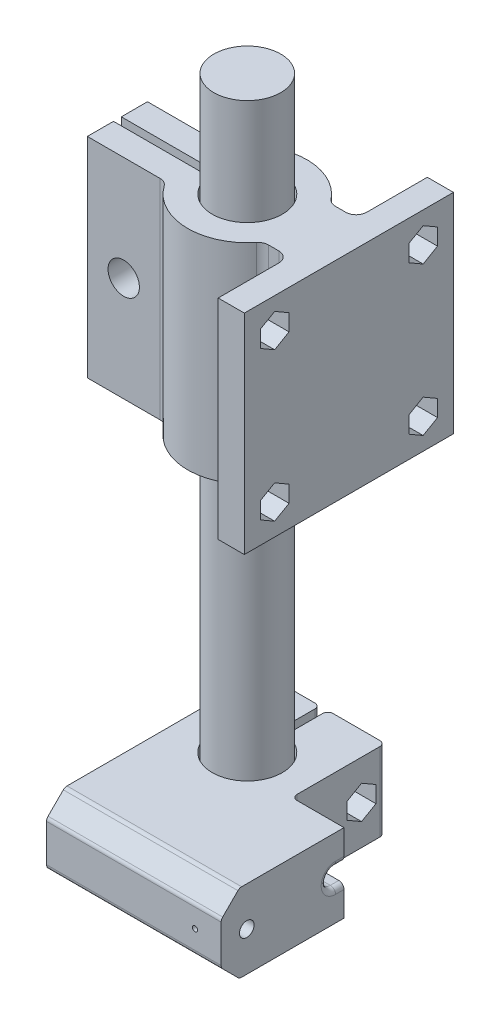
SolidWorks part; units mm, degrees
ref_plane "Front Plane" through (0, 0, 0) normal (0, 0, 1) x (1, 0, 0)
ref_plane "Top Plane" through (0, 0, 0) normal (0, 1, 0) x (1, 0, 0)
ref_plane "Right Plane" through (0, 0, 0) normal (1, 0, 0) x (0, 0, -1)
sketch "Sketch1" plane through (0, 0, 0) normal (0, 1, 0) x (1, 0, 0)
  circle A0 centre (0, 0) radius 6.4
  dimension "D1" = 12.8
extrude "Boss-Extrude1" add sketch "Sketch1" along normal blind 40 and the other way blind 80
sketch "Sketch2" plane through (0, 0, 0) normal (0, 1, 0) x (1, 0, 0)
  line L0 (-9.8437, 5.75) -> (-24.8437, 5.75)
  line L1 (-24.8437, 5.75) -> (-24.8437, 0.75)
  line L2 (0, 6.4) -> (0, 0) construction
  line L3 (-39.5441, 0) -> (14.434, 0) construction
  line L4 (9.434, -6.4) -> (14.434, -6.4)
  line L5 (-24.8437, 0.75) -> (-6.6579, 0.75)
  line L6 (-24.8437, -0.75) -> (-6.6579, -0.75)
  line L7 (-24.8437, -5.75) -> (-24.8437, -0.75)
  line L8 (-9.8437, -5.75) -> (-24.8437, -5.75)
  line L9 (14.434, -6.4) -> (14.434, 6.4)
  line L10 (14.434, 6.4) -> (9.434, 6.4)
  arc A0 (9.434, 6.4) -> (-9.8437, 5.75) centre (0, 0) ccw
  circle A1 centre (0, 0) radius 6.4 construction
  arc A2 (-6.6579, -0.75) -> (-6.6579, 0.75) centre (0, 0) ccw
  arc A3 (9.434, -6.4) -> (-9.8437, -5.75) centre (0, 0) cw
  point P13 (0, 3.2)
  point P20 (0, -3.2)
  point P21 (6.7, 0)
  dimension "D1" = 5
  dimension "D2" = 0.3
  dimension "D6" = 5
  dimension "D3" = 0.75
  dimension "D4" = 5
  dimension "D5" = 15
extrude "Boss-Extrude2" add sketch "Sketch2" along normal blind 20 and the other way blind 20 separate body
sketch "Sketch6" plane through (14.434, 0, 0) normal (1, 0, 0) x (0, 0, -1)
  line L0 (-6.4, -20) -> (6.4, -20) construction
  line L1 (-20, -20) -> (20, -20)
  line L2 (-20, -20) -> (-20, 20)
  line L3 (-20, 20) -> (20, 20)
  line L4 (20, -20) -> (20, 20)
  line L5 (-20, -20) -> (20, 20) construction
  line L6 (-20, 20) -> (20, -20) construction
  point P0 (0, 0)
  dimension "D1" = 40
extrude "Boss-Extrude6" add sketch "Sketch6" along normal blind 10
ref_plane "Plane1" through (0, 0, 0) normal (0, 0, -1) x (-1, 0, 0)
sketch "Sketch7" plane through (0, 0, 0) normal (0, 0, -1) x (-1, 0, 0)
  line L0 (0, 0) -> (-105.5276, 0) construction
  line L1 (-24.434, -6.4) -> (-29.434, -6.4)
  line L3 (-24.434, 20) -> (-24.434, -20) construction
  line L4 (-48.7116, -5.75) -> (-63.7116, -5.75)
  line L5 (-63.7116, -5.75) -> (-63.7116, -0.75)
  line L6 (-63.7116, -0.75) -> (-45.5259, -0.75)
  line L7 (-24.434, -6.4) -> (-24.434, 6.4)
  line L8 (-63.7116, 0.75) -> (-45.5259, 0.75)
  line L9 (-63.7116, 5.75) -> (-63.7116, 0.75)
  line L10 (-48.7116, 5.75) -> (-63.7116, 5.75)
  line L11 (-24.434, 6.4) -> (-29.434, 6.4)
  circle A0 centre (-38.868, 0) radius 6.4 construction
  arc A1 (-48.7116, -5.75) -> (-29.434, -6.4) centre (-38.868, 0) ccw
  arc A2 (-45.5259, -0.75) -> (-45.5259, 0.75) centre (-38.868, 0) ccw
  arc A3 (-48.7116, 5.75) -> (-29.434, 6.4) centre (-38.868, 0) cw
  point P15 (-38.868, -6.4)
  point P19 (-24.434, 0)
  point P21 (-38.868, 6.4)
  dimension "D1" = 12.8
  dimension "D2" = 5
  dimension "D4" = 0.3
  dimension "D7" = 15
  dimension "D3" = 5
  dimension "D5" = 0.75
  dimension "D6" = 5
extrude "Boss-Extrude7" add sketch "Sketch7" along normal blind 20 and the other way blind 20
fillet "Fillet4" radius 2 4 edges
fillet "Fillet5" radius 2 8 edges at (29.434, -6.4, 0) (29.434, 6.4, 0) (48.7116, 5.75, 0) (48.7116, -5.75, 0) (9.434, 0, 6.4) (9.434, 0, -6.4) (-9.8437, 0, -5.75) (-9.8437, 0, 5.75)
sketch "Sketch9" plane through (0, 0, 5.75) normal (0, 0, 1) x (1, 0, 0)
  line L0 (-10.9315, 0) -> (-24.8437, 0) construction
  line L1 (-24.8437, -20) -> (-24.8437, 20) construction
  line L3 (-10.9315, -20) -> (-10.9315, 20) construction
  circle A1 centre (-17.8876, 0) radius 3
  dimension "D1" = 6
extrude "Cut-Extrude1" cut sketch "Sketch9" against normal up to surface (11.5 mm away) up to face at (-17.8876, 0, -5.75)
sketch "Sketch10" plane through (0, -5.75, 0) normal (0, -1, 0) x (-1, 0, 0)
  line L0 (-63.7116, 0) -> (-49.7995, 0) construction
  line L1 (-63.7116, -20) -> (-63.7116, 20) construction
  line L2 (-49.7995, -20) -> (-49.7995, 20) construction
  circle A0 centre (-56.7555, 0) radius 2.5
  dimension "D1" = 5
extrude "Cut-Extrude2" cut sketch "Sketch10" against normal up to surface (11.5 mm away) up to face at (56.7555, 5.75, 0)
sketch "Sketch13" plane through (0, -80, 0) normal (0, -1, 0) x (1, 0, 0)
  line L0 (11.7, -14.6579) -> (11.7, 26.7)
  line L1 (11.7, -14.6579) -> (0.75, -14.6579)
  line L2 (0, -14.6579) -> (0, 33.0338) construction
  line L3 (-11.7, 26.7) -> (11.7, 26.7)
  line L5 (0.75, -14.6579) -> (0.75, -6.6579)
  line L6 (-0.75, -14.6579) -> (-0.75, -6.6579)
  line L8 (-11.7, -14.6579) -> (-0.75, -14.6579)
  line L9 (-11.7, -14.6579) -> (-11.7, 26.7)
  arc A0 (0.75, -6.6579) -> (-0.75, -6.6579) centre (0, 0) ccw
  circle A1 centre (0, 0) radius 6.4 construction
  point P13 (6.7, 0)
  point P18 (-6.7, 0)
  point P19 (0, 6.7)
  dimension "D1" = 0.3
  dimension "D4" = 5
  dimension "D2" = 0.75
  dimension "D3" = 8
  dimension "D5" = 20
extrude "Boss-Extrude8" add sketch "Sketch13" along normal blind 7.5 and the other way blind 7.5 separate body
sketch "Sketch22" [suppressed] plane through (0, -70, 0) normal (0, 1, 0) x (1, 0, 0)
  line L0 (-3, -26.7) -> (-11.7, -18) construction
  line L1 (3, -26.7) -> (-3, -26.7) construction
  line L2 (11.7, -18) -> (3, -26.7) construction
  line L3 (-3, -26.7) -> (-11.7, -18)
  line L4 (3, -26.7) -> (-3, -26.7)
  line L5 (11.7, -18) -> (3, -26.7)
  line L6 (-11.7, -18) -> (-11.7, -10.7)
  line L7 (-11.7, -26.7) -> (-11.7, 14.625) construction
  line L8 (-11.7, -10.7) -> (11.7, -10.7)
  line L9 (11.7, 14.625) -> (11.7, -26.7) construction
  line L10 (11.7, -10.7) -> (11.7, -18)
  arc A1 (-1, 6.625) -> (1, 6.625) centre (0, 0) ccw construction
  point P10 (0, -6.7)
  dimension "D1" = 4
extrude "Boss-Extrude10" [suppressed] add sketch "Sketch22" along normal blind 10
sketch "Sketch23" [suppressed] plane through (0, 0, 10.7) normal (0, 0, -1) x (-1, 0, 0)
  line L0 (0, -75) -> (0, -65) construction
  line L1 (-11.7, -75) -> (11.7, -75) construction
  line L2 (-11.7, -65) -> (11.7, -65) construction
  line L3 (-11.7, -65) -> (-11.7, -75) construction
  circle A0 centre (0, -70) radius 0.5
  dimension "D1" = 1
extrude "Cut-Extrude11" [suppressed] cut sketch "Sketch23" against normal up to next
sketch "Sketch24" [suppressed] plane through (0, 0, 10.7) normal (0, 0, -1) x (-1, 0, 0)
  circle A0 centre (0, -70) radius 1.75
  dimension "D1" = 3.5
extrude "Cut-Extrude12" [suppressed] cut sketch "Sketch24" against normal blind 8
sketch "Sketch25" [suppressed] plane through (0, -65, 0) normal (0, 1, 0) x (1, 0, 0)
  line L0 (0, -26.7) -> (0, -18.7) construction
  line L1 (-3, -26.7) -> (3, -26.7) construction
  line L2 (1.75, -18.7) -> (-1.75, -18.7) construction
  circle A0 centre (0, -22.7) radius 1.45
  dimension "D1" = 2.9
extrude "Cut-Extrude13" [suppressed] cut sketch "Sketch25" against normal blind 5
sketch "Sketch26" [suppressed] plane through (0, -65, 0) normal (0, 1, 0) x (1, 0, 0)
  line L0 (0, -5.5763) -> (0, -13.6517) construction
  line L2 (1.75, -5.5763) -> (1.75, -13.6517)
  line L4 (-1.75, -5.5763) -> (-1.75, -13.6517)
  arc A0 (1.75, -5.5763) -> (-1.75, -5.5763) centre (0, -5.5763) ccw
  arc A1 (-1.75, -13.6517) -> (1.75, -13.6517) centre (0, -13.6517) ccw
  point P5 (0, -9.614)
  dimension "D1" = 3.5
extrude "Cut-Extrude14" [suppressed] cut sketch "Sketch26" against normal blind 5
fillet "Fillet6" radius 1 2 edges at (-11.7, -80, -14.6579) (11.7, -80, -14.6579)
fillet "Fillet7" radius 1 2 edges at (0.75, -80, -14.6579) (-0.75, -80, -14.6579)
sketch "Sketch17" plane through (-11.7, 0, 0) normal (-1, 0, 0) x (0, 0, 1)
  line L0 (-13.6579, -80) -> (-6.6579, -80) construction
  line L3 (-6.6579, -72.5) -> (-6.6579, -87.5) construction
  line L4 (-13.6579, -72.5) -> (-13.6579, -87.5) construction
  circle A0 centre (-10.1579, -80) radius 1.55
  dimension "D1" = 3.1
extrude "Cut-Extrude8" cut sketch "Sketch17" against normal up to surface (23.4 mm away) up to face at (11.7, -80, 6.5211)
sketch "Sketch18" plane through (11.7, 0, 0) normal (1, 0, 0) x (0, 0, -1)
  line L0 (12.9079, -78.4123) -> (12.9079, -81.5877)
  line L1 (7.4079, -78.4123) -> (7.4079, -81.5877)
  line L2 (12.9079, -78.4123) -> (10.1579, -76.8246)
  line L3 (10.1579, -76.8246) -> (7.4079, -78.4123)
  line L4 (7.4079, -81.5877) -> (10.1579, -83.1754)
  line L5 (10.1579, -83.1754) -> (12.9079, -81.5877)
  line L6 (12.9079, -80) -> (7.4079, -80) construction
  circle A0 centre (10.1579, -80) radius 1.25 construction
  circle A1 centre (10.1579, -80) radius 1.55 construction
  dimension "D3" = 2.5
  dimension "D1" = 5.5
  dimension "D2" = 120
  dimension "D4" = 2.75
extrude "Cut-Extrude9" cut sketch "Sketch18" against normal blind 5
sketch "Sketch19" plane through (0, -80, 0) normal (0, -1, 0) x (-1, 0, 0)
  circle A1 centre (0, 0) radius 6.4
  circle A2 centre (0, 0) radius 6.4
  dimension "D1" = 0
extrude "Boss-Extrude9" add sketch "Sketch19" along normal blind 10
fillet "Fillet9" [suppressed] radius 1
sketch "Sketch27" plane through (11.7, 0, 0) normal (1, 0, 0) x (0, 0, -1)
  line L0 (-26.7, -80) -> (13.6579, -80) construction
  line L3 (-26.7, -72.5) -> (-26.7, -87.5) construction
  line L4 (13.6579, -87.5) -> (13.6579, -72.5) construction
  line L5 (-23.2, -72.5) -> (-26.7, -76)
  line L6 (13.6579, -72.5) -> (-26.7, -72.5) construction
  line L7 (-26.7, -76) -> (-26.7, -84)
  line L8 (-23.2, -72.5) -> (-3.2, -72.5)
  line L9 (-3.2, -72.5) -> (-3.2, -87.5)
  line L10 (-23.2, -87.5) -> (-3.2, -87.5)
  line L11 (-23.2, -87.5) -> (-26.7, -84)
  point P13 (-3.2, -80)
  dimension "D1" = 45
  dimension "D2" = 20
  dimension "D3" = 4
extrude "Boss-Extrude11" add sketch "Sketch27" along normal blind 10
sketch "Sketch28" plane through (11.7, 0, 0) normal (1, 0, 0) x (0, 0, -1)
  line L0 (-26.7, -72.5) -> (-26.7, -76) construction
  line L1 (-26.7, -76) -> (-23.2, -72.5) construction
  line L2 (-23.2, -72.5) -> (-26.7, -72.5) construction
  line L3 (-26.7, -87.5) -> (-23.2, -87.5) construction
  line L4 (-23.2, -87.5) -> (-26.7, -84) construction
  line L5 (-26.7, -84) -> (-26.7, -87.5) construction
  line L6 (-26.7, -72.5) -> (-26.7, -76)
  line L7 (-26.7, -76) -> (-23.2, -72.5)
  line L8 (-23.2, -72.5) -> (-26.7, -72.5)
  line L9 (-26.7, -87.5) -> (-23.2, -87.5)
  line L10 (-23.2, -87.5) -> (-26.7, -84)
  line L11 (-26.7, -84) -> (-26.7, -87.5)
extrude "Cut-Extrude15" cut sketch "Sketch28" against normal up to next (23.4 mm away)
sketch "Sketch29" plane through (0, 0, 3.2) normal (0, 0, -1) x (-1, 0, 0)
  line L0 (-11.7, -80) -> (-21.7, -80) construction
  line L1 (-11.7, -87.5) -> (-11.7, -72.5) construction
  line L2 (-21.7, -87.5) -> (-21.7, -72.5) construction
  circle A0 centre (-16.7, -80) radius 0.5
  dimension "D1" = 1
extrude "Cut-Extrude16" cut sketch "Sketch29" against normal up to next (23.5 mm away)
sketch "Sketch30" plane through (0, 0, 3.2) normal (0, 0, -1) x (-1, 0, 0)
  circle A0 centre (-16.7, -80) radius 1.75
  dimension "D1" = 3.5
extrude "Cut-Extrude17" cut sketch "Sketch30" against normal blind 8
fillet "Fillet10" radius 1 5 edges at (5, -87.5, 23.2) (5, -84, 26.7) (5, -76, 26.7) (5, -72.5, 23.2) (11.7, -80, 3.2)
sketch "Sketch31" plane through (21.7, 0, 0) normal (1, 0, 0) x (0, 0, -1)
  line L0 (-3.2, -80) -> (-26.7, -80) construction
  line L1 (-3.2, -87.5) -> (-3.2, -72.5) construction
  line L2 (-26.7, -76.4142) -> (-26.7, -83.5858) construction
  circle A0 centre (-21.7969, -80) radius 1.4
  dimension "D1" = 2.8
extrude "Cut-Extrude18" cut sketch "Sketch31" against normal blind 5
sketch "Sketch32" plane through (21.7, 0, 0) normal (1, 0, 0) x (0, 0, -1)
  line L0 (-1.3874, -80) -> (-4.8189, -80) construction
  line L2 (-1.3874, -81.75) -> (-4.8189, -81.75)
  line L3 (-1.3874, -78.25) -> (-4.8189, -78.25)
  arc A0 (-1.3874, -81.75) -> (-1.3874, -78.25) centre (-1.3874, -80) ccw
  arc A1 (-4.8189, -78.25) -> (-4.8189, -81.75) centre (-4.8189, -80) ccw
  point P4 (-3.1032, -80)
  dimension "D1" = 3.5
extrude "Cut-Extrude19" cut sketch "Sketch32" against normal blind 5
fillet "Fillet11" radius 1 3 edges at (21.7, -81.75, 4.0095) (21.7, -80, 6.5689) (21.7, -78.25, 4.0095)
sketch "Sketch33" plane through (14.434, 0, 0) normal (-1, 0, 0) x (0, 0, 1)
  line L0 (14.2, 20) -> (14.2, 8.4) construction
  line L1 (8.4, 20) -> (20, 20) construction
  line L2 (20, 8.4) -> (-20, 8.4) construction
  line L3 (20, 0) -> (8.4, 0) construction
  line L4 (20, 20) -> (20, -20) construction
  line L5 (8.4, 20) -> (8.4, -20) construction
  line L6 (0, 20) -> (0, -20) construction
  line L7 (-5.75, -20) -> (-0.75, -20) construction
  line L8 (-5.75, 20) -> (-0.75, 20) construction
  circle A0 centre (14.2, 14.2) radius 1.5
  circle A1 centre (14.2, -14.2) radius 1.5
  circle A2 centre (-14.2, -14.2) radius 1.5
  circle A3 centre (-14.2, 14.2) radius 1.5
  dimension "D1" = 3
extrude "Cut-Extrude20" cut sketch "Sketch33" against normal blind 10
sketch "Sketch34" plane through (14.434, 0, 0) normal (-1, 0, 0) x (0, 0, 1)
  line L0 (16.95, -12.6123) -> (16.95, -15.7877)
  line L1 (11.45, -12.6123) -> (11.45, -15.7877)
  line L2 (16.95, -12.6123) -> (14.2, -11.0246)
  line L3 (14.2, -11.0246) -> (11.45, -12.6123)
  line L4 (11.45, -15.7877) -> (14.2, -17.3754)
  line L5 (14.2, -17.3754) -> (16.95, -15.7877)
  line L6 (16.95, -14.2) -> (11.45, -14.2) construction
  line L7 (20, 0) -> (8.4, 0) construction
  line L8 (20, 20) -> (20, -20) construction
  line L9 (8.4, 20) -> (8.4, -20) construction
  line L10 (16.95, 14.2) -> (11.45, 14.2) construction
  line L11 (14.2, 17.3754) -> (16.95, 15.7877)
  line L12 (11.45, 15.7877) -> (14.2, 17.3754)
  line L13 (14.2, 11.0246) -> (11.45, 12.6123)
  line L14 (16.95, 12.6123) -> (14.2, 11.0246)
  line L15 (11.45, 12.6123) -> (11.45, 15.7877)
  line L16 (16.95, 12.6123) -> (16.95, 15.7877)
  line L17 (0, 20) -> (0, -20) construction
  line L18 (-5.75, -20) -> (-0.75, -20) construction
  line L19 (-5.75, 20) -> (-0.75, 20) construction
  line L20 (-16.95, -14.2) -> (-11.45, -14.2) construction
  line L21 (-14.2, -17.3754) -> (-16.95, -15.7877)
  line L22 (-11.45, -15.7877) -> (-14.2, -17.3754)
  line L23 (-14.2, -11.0246) -> (-11.45, -12.6123)
  line L24 (-16.95, -12.6123) -> (-14.2, -11.0246)
  line L25 (-11.45, -12.6123) -> (-11.45, -15.7877)
  line L26 (-16.95, -12.6123) -> (-16.95, -15.7877)
  line L27 (-16.95, 14.2) -> (-11.45, 14.2) construction
  line L28 (-16.95, 12.6123) -> (-16.95, 15.7877)
  line L29 (-11.45, 12.6123) -> (-11.45, 15.7877)
  line L30 (-16.95, 12.6123) -> (-14.2, 11.0246)
  line L31 (-14.2, 11.0246) -> (-11.45, 12.6123)
  line L32 (-11.45, 15.7877) -> (-14.2, 17.3754)
  line L33 (-14.2, 17.3754) -> (-16.95, 15.7877)
  circle A0 centre (14.2, -14.2) radius 1.25 construction
  circle A1 centre (14.2, -14.2) radius 1.5 construction
  circle A2 centre (14.2, 14.2) radius 1.25 construction
  circle A3 centre (-14.2, -14.2) radius 1.25 construction
  circle A4 centre (-14.2, 14.2) radius 1.25 construction
  dimension "D3" = 2.5
  dimension "D1" = 5.5
  dimension "D2" = 120
  dimension "D4" = 2.75
extrude "Cut-Extrude21" cut sketch "Sketch34" against normal blind 5
ref_plane "Plane2" through (19.434, 0, 0) normal (-1, 0, 0) x (0, 0, 1)
sketch "Sketch35" plane through (19.434, 0, 0) normal (-1, 0, 0) x (0, 0, 1)
  line L1 (-38.282, 26.8973) -> (38.282, 26.8973)
  line L2 (-38.282, 26.8973) -> (-38.282, -26.8973)
  line L3 (-38.282, -26.8973) -> (38.282, -26.8973)
  line L4 (38.282, 26.8973) -> (38.282, -26.8973)
  line L5 (-38.282, 26.8973) -> (38.282, -26.8973) construction
  line L6 (-38.282, -26.8973) -> (38.282, 26.8973) construction
  point P0 (0, 0)
extrude "Cut-Extrude22" cut sketch "Sketch35" against normal blind 68
